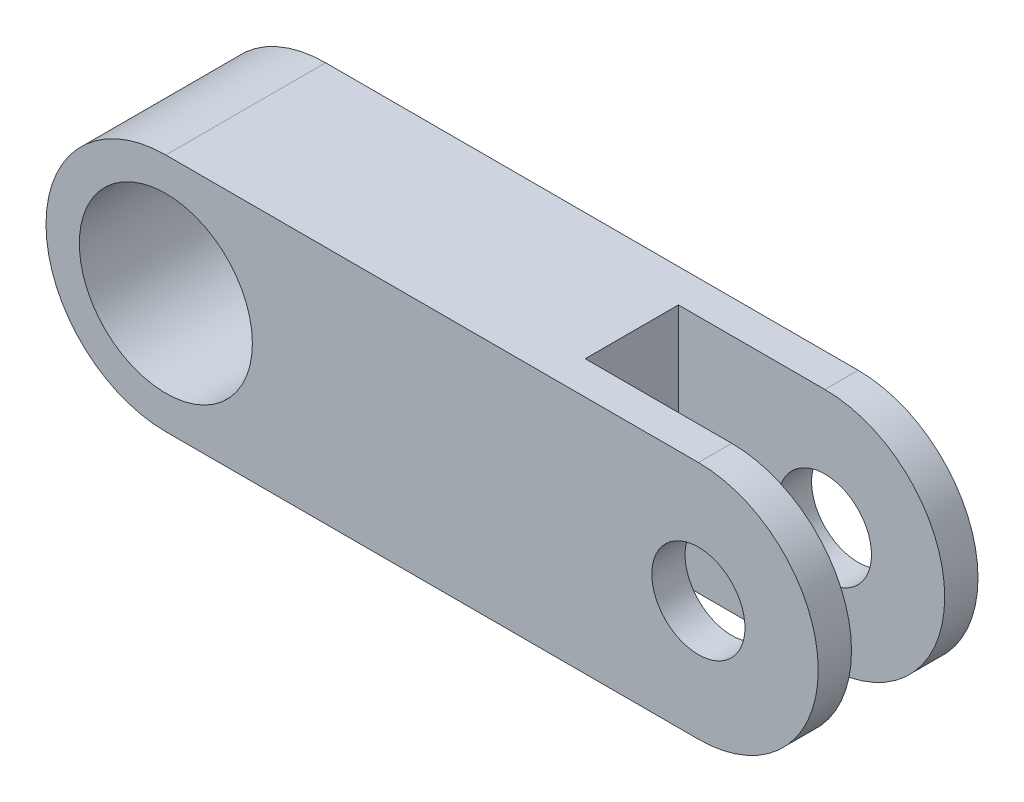
SolidWorks part; units mm, degrees
ref_plane "Front Plane" through (0, 0, 0) normal (0, 0, 1) x (1, 0, 0)
ref_plane "Top Plane" through (0, 0, 0) normal (0, 1, 0) x (1, 0, 0)
ref_plane "Right Plane" through (0, 0, 0) normal (1, 0, 0) x (0, 0, -1)
sketch "Sketch1" plane through (0, 0, 0) normal (0, 0, 1) x (1, 0, 0)
  line L0 (-10, 0) -> (10, 0) construction
  line L1 (-10, 4.5) -> (10, 4.5)
  line L2 (-10, -4.5) -> (10, -4.5)
  arc A0 (-10, 4.5) -> (-10, -4.5) centre (-10, 0) ccw
  arc A1 (10, -4.5) -> (10, 4.5) centre (10, 0) ccw
  circle A2 centre (-10, 0) radius 3.25
  circle A3 centre (10, 0) radius 1.75
  point P3 (0, 0)
  dimension "5.5" = 6.5
  dimension "D2" = 4.5
  dimension "D4" = 3.5
  dimension "D3" = 20
extrude "Boss-Extrude1" add sketch "Sketch1" along normal mid plane 6
sketch "Sketch5" plane through (0, 0, 0) normal (0, 0, 1) x (1, 0, 0)
  line L0 (10, 4.5) -> (-10, 4.5) construction
  line L1 (4.5, 4.5) -> (14.5, 4.5)
  line L2 (4.5, 4.5) -> (4.5, -4.5)
  line L3 (4.5, -4.5) -> (14.5, -4.5)
  line L4 (14.5, 4.5) -> (14.5, -4.5)
  line L5 (-10, -4.5) -> (10, -4.5) construction
  arc A0 (10, -4.5) -> (10, 4.5) centre (10, 0) ccw construction
  dimension "D1" = 10
extrude "Cut-Extrude1" cut sketch "Sketch5" against normal mid plane 3.5
